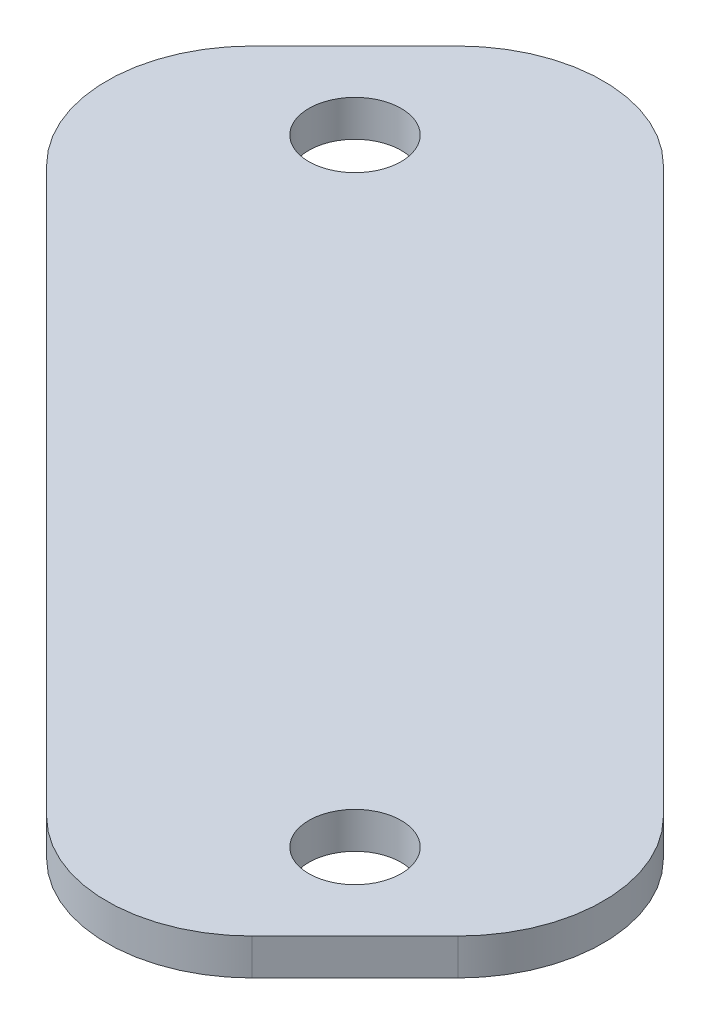
SolidWorks part; units mm, degrees
ref_plane "Front Plane" through (0, 0, 0) normal (0, 0, 1) x (1, 0, 0)
ref_plane "Top Plane" through (0, 0, 0) normal (0, 1, 0) x (1, 0, 0)
ref_plane "Right Plane" through (0, 0, 0) normal (1, 0, 0) x (0, 0, -1)
sketch "Sketch1" plane through (0, 0, 0) normal (0, 1, 0) x (1, 0, 0)
  line L5 (-148.4924, 63.6396) -> (63.6396, -148.4924)
  line L6 (63.6396, -148.4924) -> (148.4924, -63.6396)
  line L8 (-148.4924, 63.6396) -> (-63.6396, 148.4924)
  line L9 (63.6396, -148.4924) -> (148.4924, -63.6396)
  line L18 (-63.6396, 148.4924) -> (148.4924, -63.6396)
  line L19 (0, 0) -> (-106.066, 106.066) construction
  line L20 (0, 0) -> (106.066, -106.066) construction
  line L21 (0, 0) -> (42.4264, 42.4264) construction
  line L22 (0, 0) -> (0, 84.8528) construction
  point P2 (0, 0)
  point P15 (-106.066, 106.066)
  point P18 (106.066, -106.066)
  dimension "D1" = 300
  dimension "D2" = 120
  dimension "D3" = 45
extrude "Boss-Extrude1" add sketch "Sketch1" along normal blind 10 contours L18 L8 L5 L6
sketch "Sketch2" plane through (0, 10, 0) normal (0, 1, 0) x (1, 0, 0)
  line L0 (84.8528, -84.8528) -> (-84.8528, 84.8528) construction
  line L1 (-63.6396, 148.4924) -> (148.4924, -63.6396) construction
  line L2 (-148.4924, 63.6396) -> (-63.6396, 148.4924) construction
  circle A0 centre (-84.8528, 84.8528) radius 12.7
  circle A1 centre (84.8528, -84.8528) radius 12.7
  point P4 (0, 0)
  dimension "D2" = 25.4
  dimension "D1" = 30
extrude "Cut-Extrude1" cut sketch "Sketch2" against normal blind 10
fillet "Fillet1" radius 40 4 edges at (63.6396, 5, 148.4924) (148.4924, 5, 63.6396) (-148.4924, 5, -63.6396) (-63.6396, 5, -148.4924)
